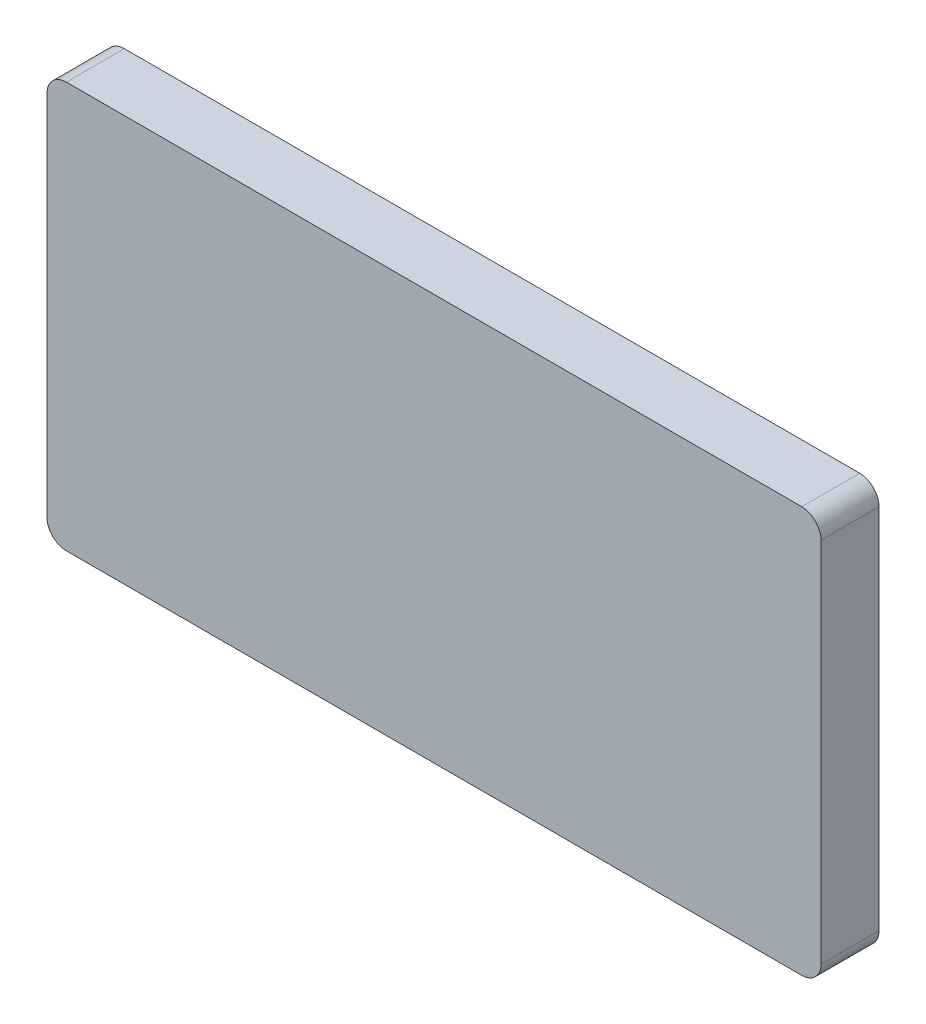
SolidWorks part; units mm, degrees
ref_plane "Front Plane" through (0, 0, 0) normal (0, 0, 1) x (1, 0, 0)
ref_plane "Top Plane" through (0, 0, 0) normal (0, 1, 0) x (1, 0, 0)
ref_plane "Right Plane" through (0, 0, 0) normal (1, 0, 0) x (0, 0, -1)
sketch "Sketch1" plane through (0, 0, 0) normal (0, 0, 1) x (1, 0, 0)
  line L0 (0, 0) -> (-36, 0) construction
  line L1 (-36, 21) -> (44.1, 21)
  line L2 (-36, 21) -> (-36, -21)
  line L3 (-36, -21) -> (44.1, -21)
  line L4 (44.1, 21) -> (44.1, -21)
  line L5 (44.1, -19) -> (44.1, 19) construction
  line L6 (-36, 19) -> (-36, -19) construction
  line L7 (42.1, 21) -> (-34, 21) construction
extrude "Boss-Extrude1" add sketch "Sketch1" along normal blind 6
sketch "Sketch2" plane through (0, 0, 0) normal (0, 0, -1) x (-1, 0, 0)
  line L8 (34, -19) -> (34, 19)
  line L9 (34, 19) -> (-42.1, 19)
  line L10 (-42.1, 19) -> (-42.1, -19)
  line L11 (-42.1, -19) -> (34, -19)
  line L12 (34, -19) -> (34, 19)
  line L13 (34, 19) -> (-42.1, 19)
  line L14 (-42.1, 19) -> (-42.1, -19)
  line L15 (-42.1, -19) -> (34, -19)
  dimension "D1" = 2
extrude "Cut-Extrude1" cut sketch "Sketch2" against normal offset from surface (5.4 mm away) 0.6 up to face at (4.05, 0, 6)
fillet "Fillet1" radius 2 4 edges at (44.1, 21, 3) (44.1, -21, 3) (-36, 21, 3) (-36, -21, 3)
